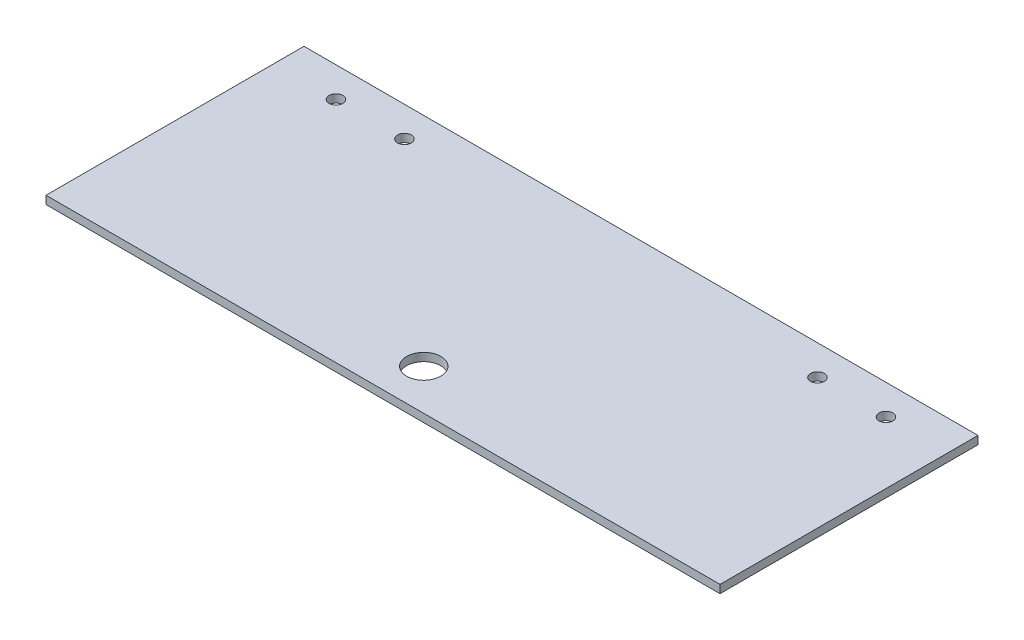
SolidWorks part; units mm, degrees
ref_plane "Front Plane" through (0, 0, 0) normal (0, 0, 1) x (1, 0, 0)
ref_plane "Top Plane" through (0, 0, 0) normal (0, 1, 0) x (1, 0, 0)
ref_plane "Right Plane" through (0, 0, 0) normal (1, 0, 0) x (0, 0, -1)
sketch "Sketch1" plane through (0, 0, 0) normal (0, 1, 0) x (1, 0, 0)
  line L0 (125, 95.7) -> (125, 0) construction
  line L1 (0, 95.7) -> (250, 95.7)
  line L2 (0, 95.7) -> (0, 0)
  line L3 (0, 0) -> (250, 0)
  line L4 (250, 95.7) -> (250, 0)
  circle A0 centre (23, 84.56) radius 2.564
  circle A1 centre (48.4, 84.56) radius 2.564
  circle A2 centre (201.6, 84.56) radius 2.564
  circle A3 centre (227, 84.56) radius 2.564
  circle A4 centre (125, 15.1) radius 6.35
  dimension "D2" = 5.128
  dimension "D7" = 12.7
  dimension "D8" = 15.1
  dimension "D1" = 250
  dimension "D3" = 25.4
  dimension "D4" = 23
  dimension "D5" = 11.14
  dimension "D6" = 84.56
extrude "Boss-Extrude1" add sketch "Sketch1" along normal blind 3
equation "\"cf_tube_outer_diameter\"= 25mm"
equation "\"cf_tube_inner_diameter\" = 21mm"
equation "\"mid_plate_mid_to_top\" = 100mm"
equation "\"mid_plate_mid_to_bottom\" = 30mm"
equation "\"mid_plate_horizontal_spacing\"=250mm"
equation "\"cf_plate_thickness\" =4mm"
equation "\"mid_tube_length\" = 500mm"
equation "\"mid_plate_bottom_width\" = 180mm"
equation "\"mid_support_plate_distance\" = 250mm"
equation "\"nut_strip_2_hole_distance\" = 7mm"
equation "\"nut_strip_hole_diameter\" = 2.5mm"
equation "\"nut_strip_hole_to_edge_distance\"= 2.5mm"
